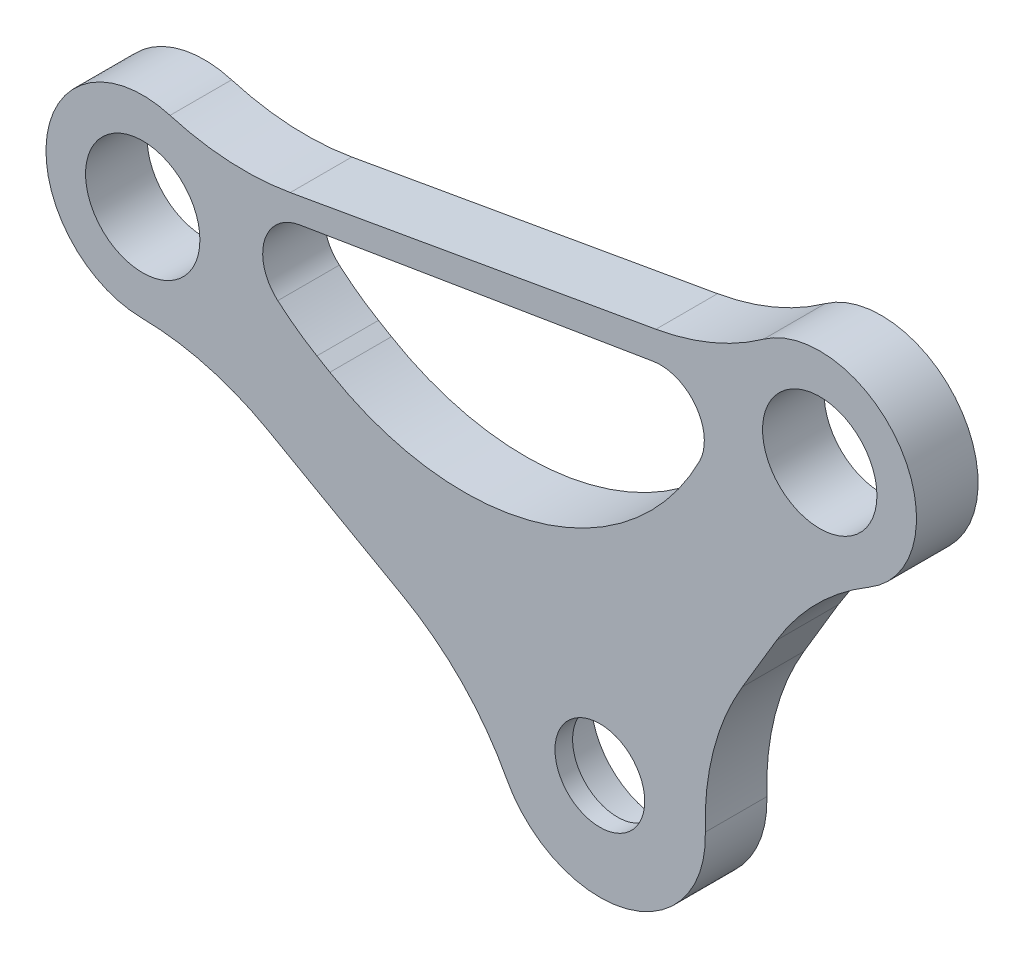
SolidWorks part; units mm, degrees
ref_plane "前视基准面" through (0, 0, 0) normal (0, 0, 1) x (1, 0, 0)
ref_plane "上视基准面" through (0, 0, 0) normal (0, 1, 0) x (1, 0, 0)
ref_plane "右视基准面" through (0, 0, 0) normal (1, 0, 0) x (0, 0, -1)
sketch "草图1" plane through (0, 0, 0) normal (0, 0, 1) x (1, 0, 0)
  line B0 (20.1088, 23.3736) -> (16.2034, 16.8201)
  line B1 (-22.3872, 6.4819) -> (-37.7418, 15.1372)
  line B2 (-35.1891, 39.7915) -> (6.3803, 47.1213)
  line B3 (6.0606, 43.804) -> (-34.1435, 37.1395)
  line B4 (-30.6863, 24.352) -> (-32.1625, 25.2246)
  circle B5 centre (25, 43.3013) radius 6.5
  circle B6 centre (-51.9615, 30) radius 6.5
  circle B7 centre (0, 0) radius 5.1
  circle B8 centre (0, 0) radius 8 construction
  arc B9 (16.2034, 16.8201) -> (11.9927, 0.4179) centre (41.9745, 1.4627) ccw
  arc B10 (-10.6053, -5.6149) -> (11.9927, 0.4179) centre (0, 0) ccw
  arc B11 (-10.6053, -5.6149) -> (-22.3872, 6.4819) centre (-37.1187, -19.652) ccw
  arc B12 (-48.8593, 40.5535) -> (-52.0988, 19.0009) centre (-51.9615, 30) ccw
  arc B13 (-48.8593, 40.5535) -> (-35.1891, 39.7915) centre (-40.3986, 69.3357) ccw
  arc B14 (-37.7418, 15.1372) -> (-52.0988, 19.0009) centre (-52.4733, -10.9968) ccw
  arc B15 (6.3803, 47.1213) -> (18.6068, 52.2527) centre (1.1709, 76.6655) ccw
  arc B16 (30.6019, 33.8346) -> (18.6068, 52.2527) centre (25, 43.3013) ccw
  arc B17 (30.6019, 33.8346) -> (20.1088, 23.3736) centre (45.8799, 8.0163) ccw
  arc B18 (11.3378, 36.6102) -> (6.0606, 43.804) centre (6.8783, 38.8713) ccw
  arc B19 (-34.1435, 37.1395) -> (-36.6119, 28.4383) centre (-33.3258, 32.2068) ccw
  arc B20 (-36.6119, 28.4383) -> (-32.1625, 25.2246) centre (-16.8955, 51.0494) ccw
  arc B21 (-30.6863, 24.352) -> (11.3378, 36.6102) centre (-15.4194, 50.1768) ccw
sketch_block_instance "MISCPARTS5-1"
sketch_block "MISCPARTS5"
sketch "草图3" plane through (0, 0, 0) normal (0, 0, 1) x (1, 0, 0)
  line L0 (-22.3872, 6.4819) -> (-37.7418, 15.1372) construction
  line L1 (20.1088, 23.3736) -> (16.2034, 16.8201) construction
  line L2 (-35.1891, 39.7915) -> (6.3803, 47.1213) construction
  line L3 (6.0606, 43.804) -> (-34.1435, 37.1395) construction
  line L4 (-22.3872, 6.4819) -> (-37.7418, 15.1372)
  line L5 (20.1088, 23.3736) -> (16.2034, 16.8201)
  line L6 (-35.1891, 39.7915) -> (6.3803, 47.1213)
  line L7 (6.0606, 43.804) -> (-34.1435, 37.1395)
  line L8 (-30.6863, 24.352) -> (-32.1625, 25.2246) construction
  line L9 (-30.6863, 24.352) -> (-32.1625, 25.2246)
  arc A0 (-48.8593, 40.5535) -> (-35.1891, 39.7915) centre (-40.3986, 69.3357) ccw construction
  arc A1 (-48.8593, 40.5535) -> (-52.0988, 19.0009) centre (-51.9615, 30) ccw construction
  circle A2 centre (-51.9615, 30) radius 6.5 construction
  arc A3 (-37.7418, 15.1372) -> (-52.0988, 19.0009) centre (-52.4733, -10.9968) ccw construction
  arc A4 (-10.6053, -5.6149) -> (-22.3872, 6.4819) centre (-37.1187, -19.652) ccw construction
  arc A5 (-10.6053, -5.6149) -> (11.9927, 0.4179) centre (0, 0) ccw construction
  arc A6 (16.2034, 16.8201) -> (11.9927, 0.4179) centre (41.9745, 1.4627) ccw construction
  arc A7 (30.6019, 33.8346) -> (20.1088, 23.3736) centre (45.8799, 8.0163) ccw construction
  arc A8 (30.6019, 33.8346) -> (18.6068, 52.2527) centre (25, 43.3013) ccw construction
  circle A9 centre (25, 43.3013) radius 6.5 construction
  arc A10 (6.3803, 47.1213) -> (18.6068, 52.2527) centre (1.1709, 76.6655) ccw construction
  arc A11 (-30.6863, 24.352) -> (11.3378, 36.6102) centre (-15.4194, 50.1768) ccw construction
  arc A12 (11.3378, 36.6102) -> (6.0606, 43.804) centre (6.8783, 38.8713) ccw construction
  arc A13 (-34.1435, 37.1395) -> (-36.6119, 28.4383) centre (-33.3258, 32.2068) ccw construction
  arc A14 (-36.6119, 28.4383) -> (-32.1625, 25.2246) centre (-16.8955, 51.0494) ccw construction
  circle A15 centre (0, 0) radius 5.1 construction
  arc A16 (-48.8593, 40.5535) -> (-35.1891, 39.7915) centre (-40.3986, 69.3357) ccw
  arc A17 (-48.8593, 40.5535) -> (-52.0988, 19.0009) centre (-51.9615, 30) ccw
  circle A18 centre (-51.9615, 30) radius 6.5
  arc A19 (-37.7418, 15.1372) -> (-52.0988, 19.0009) centre (-52.4733, -10.9968) ccw
  arc A20 (-10.6053, -5.6149) -> (-22.3872, 6.4819) centre (-37.1187, -19.652) ccw
  arc A21 (-10.6053, -5.6149) -> (11.9927, 0.4179) centre (0, 0) ccw
  arc A22 (16.2034, 16.8201) -> (11.9927, 0.4179) centre (41.9745, 1.4627) ccw
  arc A23 (30.6019, 33.8346) -> (20.1088, 23.3736) centre (45.8799, 8.0163) ccw
  arc A24 (30.6019, 33.8346) -> (18.6068, 52.2527) centre (25, 43.3013) ccw
  circle A25 centre (25, 43.3013) radius 6.5
  arc A26 (6.3803, 47.1213) -> (18.6068, 52.2527) centre (1.1709, 76.6655) ccw
  arc A27 (-30.6863, 24.352) -> (11.3378, 36.6102) centre (-15.4194, 50.1768) ccw
  arc A28 (11.3378, 36.6102) -> (6.0606, 43.804) centre (6.8783, 38.8713) ccw
  arc A29 (-34.1435, 37.1395) -> (-36.6119, 28.4383) centre (-33.3258, 32.2068) ccw
  arc A30 (-36.6119, 28.4383) -> (-32.1625, 25.2246) centre (-16.8955, 51.0494) ccw
  circle A31 centre (0, 0) radius 5.1
extrude "凸台-拉伸1" add sketch "草图3" along normal blind 7
sketch "草图4" plane through (0, 0, 0) normal (0, 0, -1) x (-1, 0, 0)
  circle A0 centre (0, 0) radius 8 construction
  circle A1 centre (0, 0) radius 8
extrude "切除-拉伸1" cut sketch "草图4" against normal blind 5
